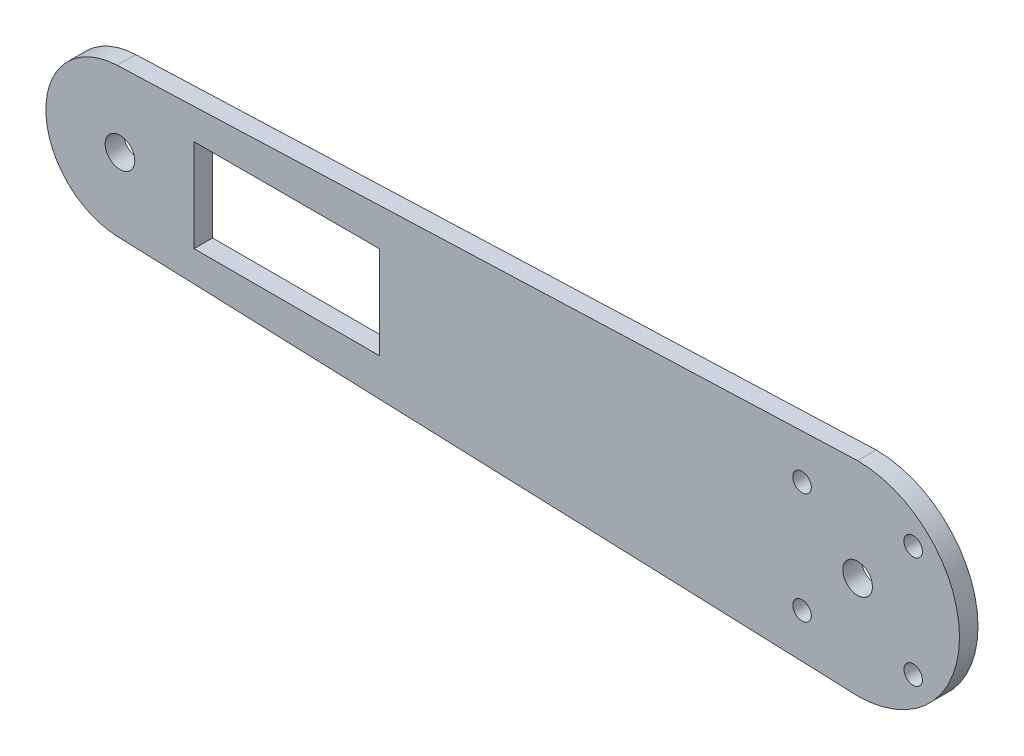
SolidWorks part; units mm, degrees
material "Custom Plastic"
ref_plane "Front Plane" through (0, 0, 0) normal (0, 0, 1) x (1, 0, 0)
ref_plane "Top Plane" through (0, 0, 0) normal (0, 1, 0) x (1, 0, 0)
ref_plane "Right Plane" through (0, 0, 0) normal (1, 0, 0) x (0, 0, -1)
sketch "Sketch1" plane through (0, 0, 0) normal (0, 0, 1) x (1, 0, 0)
  line L0 (-15, -15) -> (15, 15) construction
  line L1 (-15, -15) -> (15, -15) construction
  line L2 (-15, -15) -> (-15, 15) construction
  line L3 (-15, 15) -> (15, 15) construction
  line L4 (15, -15) -> (15, 15) construction
  line L5 (0, 27.5) -> (-199.8588, 19.9859)
  line L6 (-129.1074, -12.5) -> (-179.1074, 12.5) construction
  line L7 (-199.8588, -19.9859) -> (0, -27.5)
  line L8 (-129.1074, -12.5) -> (-179.1074, -12.5)
  line L9 (-129.1074, -12.5) -> (-129.1074, 12.5)
  line L10 (-129.1074, 12.5) -> (-179.1074, 12.5)
  line L11 (-179.1074, -12.5) -> (-179.1074, 12.5)
  arc A0 (0, -27.5) -> (0, 27.5) centre (0, 0) ccw
  circle A1 centre (-15, -15) radius 2.5
  circle A2 centre (15, 15) radius 2.5
  circle A3 centre (15, -15) radius 2.5
  circle A4 centre (-15, 15) radius 2.5
  arc A5 (-199.8588, 19.9859) -> (-199.8588, -19.9859) centre (-199.1074, 0) ccw
  circle A7 centre (0, 0) radius 4
  circle A8 centre (-199.1074, 0) radius 4
  point P11 (0, 0)
  point P22 (-154.1074, 0)
  dimension "D1" = 55
  dimension "D2" = 5
  dimension "D5" = 20
  dimension "D6" = 8
  dimension "D7" = 8
  dimension "D3" = 30
  dimension "D4" = 200
  dimension "D8" = 25
  dimension "D9" = 50
  dimension "D10" = 20
extrude "Boss-Extrude1" add sketch "Sketch1" along normal blind 5
